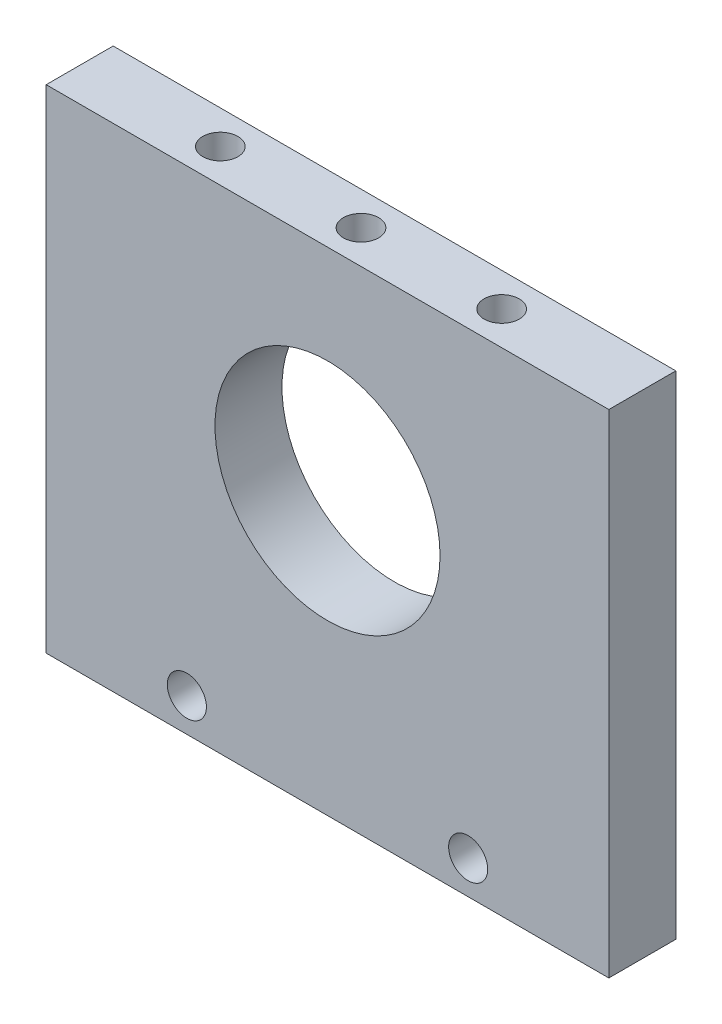
SolidWorks part; units mm, degrees
ref_plane "Plano frontal" through (0, 0, 0) normal (0, 0, 1) x (1, 0, 0)
ref_plane "Plano superior" through (0, 0, 0) normal (0, 1, 0) x (1, 0, 0)
ref_plane "Plano direito" through (0, 0, 0) normal (1, 0, 0) x (0, 0, -1)
sketch "Esboço1" plane through (0, 0, 0) normal (0, 0, 1) x (1, 0, 0)
  line L0 (0, 0) -> (0, 53.9351) construction
  line L1 (40, 35) -> (-40, -35) construction
  line L4 (40, 35) -> (-40, 35)
  line L23 (-40, 35) -> (-40, -35)
  line L24 (-40, -35) -> (40, -35)
  line L25 (40, -35) -> (40, 35)
  dimension "D1" = 40
  dimension "D2" = 40
  dimension "D3" = 35
  dimension "D4" = 40
extrude "Ressalto-extrusão1" add sketch "Esboço1" along normal blind 9.525
sketch "Esboço2" plane through (0, 0, 9.525) normal (0, 0, 1) x (1, 0, 0)
  circle A0 centre (0, 5) radius 16
  dimension "D1" = 32
  dimension "D2" = 40
  dimension "D3" = 30
extrude "Corte-extrusão1" cut sketch "Esboço2" against normal blind 10
sketch "Esboço4" plane through (0, 35, 0) normal (0, 1, 0) x (1, 0, 0)
  line L0 (-40, -4.7625) -> (40, -4.7625) construction
  line L1 (-40, -9.525) -> (-40, 0) construction
  line L2 (40, -9.525) -> (40, 0) construction
  line L3 (0, 0) -> (0, -9.525) construction
  line L4 (40, -9.525) -> (-40, -9.525) construction
  line L5 (38.5613, -4.7625) -> (-38.5613, -4.7625) construction
  circle A0 centre (20, -4.7625) radius 2.5
  circle A1 centre (0, -4.7625) radius 2.5
  circle A2 centre (-20, -4.7625) radius 2.5
  dimension "D3" = 5
  dimension "D4" = 5
  dimension "D5" = 5
  dimension "D1" = 20
  dimension "D2" = 20
extrude "Corte-extrusão3" cut sketch "Esboço4" against normal blind 23
sketch "Esboço5" plane through (0, 0, 9.525) normal (0, 0, 1) x (1, 0, 0)
  line L0 (-40, -30.24) -> (40, -30.24) construction
  line L1 (-40, 35) -> (-40, -35) construction
  line L2 (40, -35) -> (40, 35) construction
  line L3 (0, 0) -> (0, -35) construction
  line L4 (-40, -35) -> (40, -35) construction
  circle A0 centre (-20, -30.24) radius 2.78
  circle A1 centre (20, -30.24) radius 2.78
  dimension "D2" = 5.56
  dimension "D1" = 4.76
  dimension "D3" = 20
extrude "Corte-extrusão4" cut sketch "Esboço5" against normal up to surface (9.525 mm away) up to face at (16, 5, 0)
